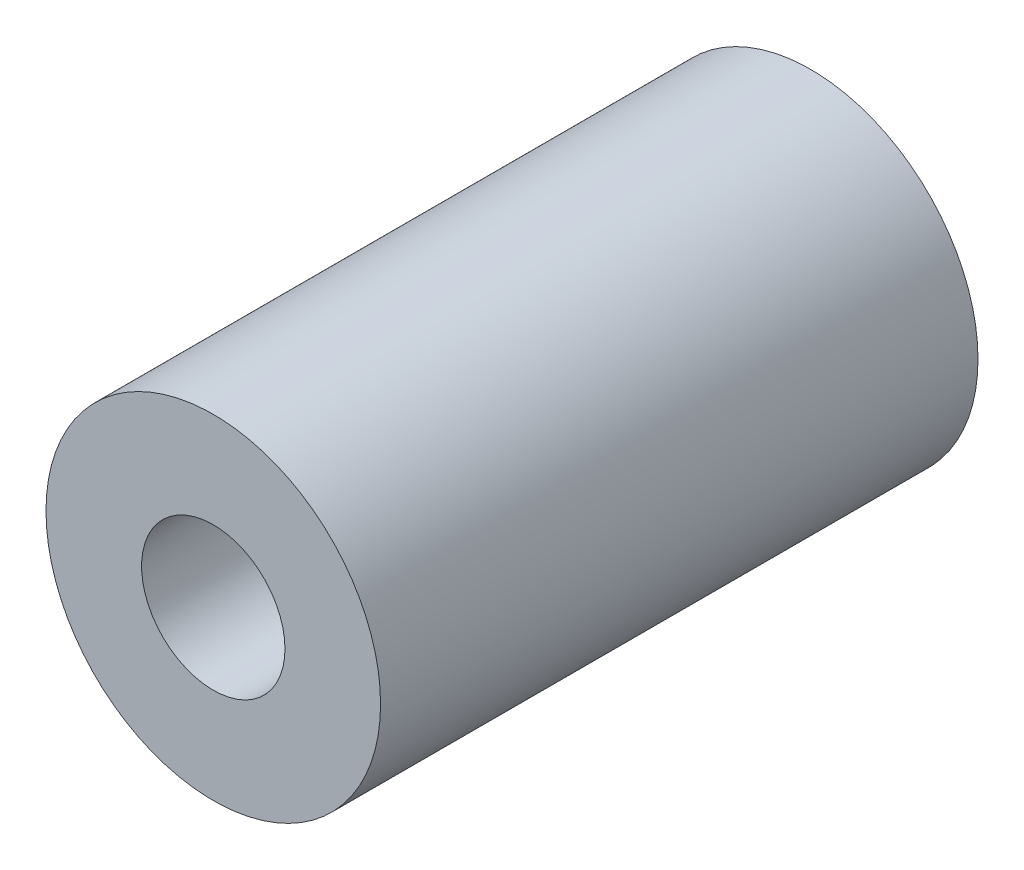
SolidWorks part; units mm, degrees
material "1060 Alloy"
ref_plane "Front Plane" through (0, 0, 0) normal (1, 0, 0) x (0, 1, 0)
ref_plane "Top Plane" through (0, 0, 0) normal (0, 0, 1) x (0, 1, 0)
ref_plane "Right Plane" through (0, 0, 0) normal (0, 1, 0) x (-1, 0, 0)
sketch "Sketch1" plane through (0, 0, 0) normal (0, 0, 1) x (0, 1, 0)
  circle A0 centre (0, 0) radius 7
  circle A1 centre (0, 0) radius 3
  dimension "D1" = 6
  dimension "D2" = 14
extrude "Boss-Extrude1" add sketch "Sketch1" along normal blind 25
